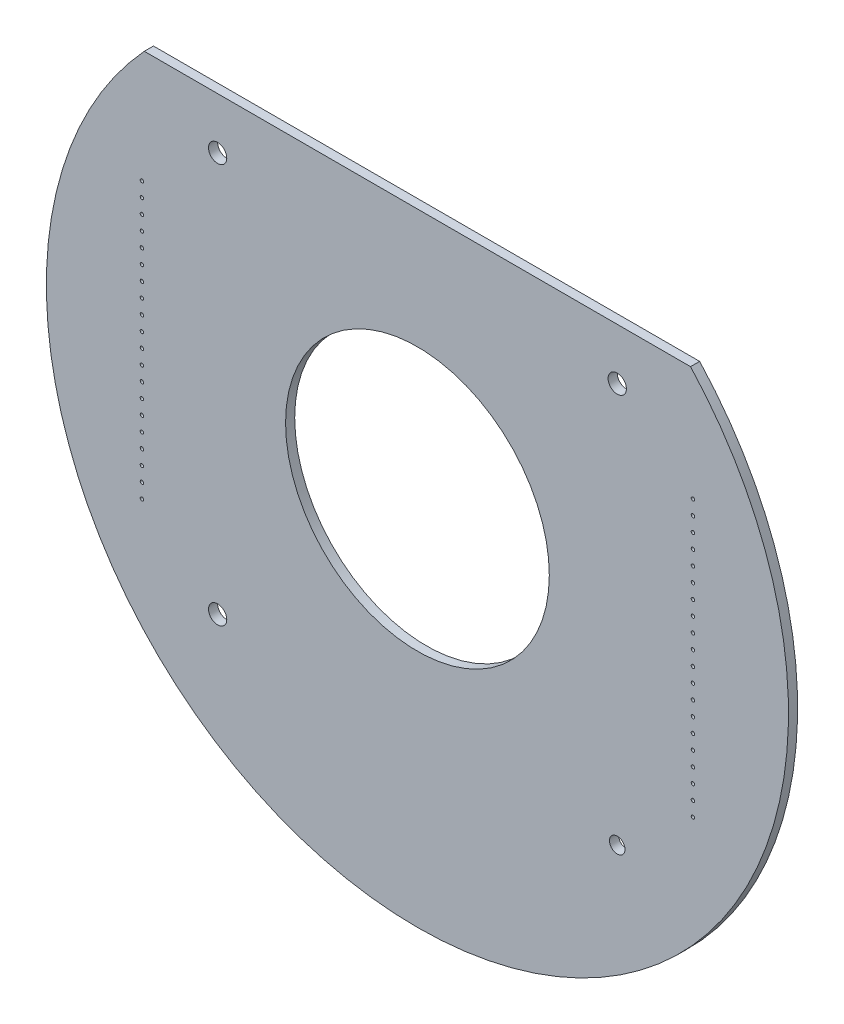
SolidWorks part; units mm, degrees
ref_plane "Front Plane" through (0, 0, 0) normal (0, 0, 1) x (1, 0, 0)
ref_plane "Top Plane" through (0, 0, 0) normal (0, 1, 0) x (1, 0, 0)
ref_plane "Right Plane" through (0, 0, 0) normal (1, 0, 0) x (0, 0, -1)
sketch "Sketch1" plane through (0, 0, 0) normal (0, 0, 1) x (1, 0, 0)
  circle A25 centre (0, 0) radius 65
extrude "Boss-Extrude1" add sketch "Sketch1" along normal blind 1.6
sketch "Sketch3" plane through (0, 0, 1.6) normal (0, 0, 1) x (1, 0, 0)
  circle A0 centre (48.26, -24.13) radius 0.3
  circle A1 centre (-48.26, -24.13) radius 0.3
  circle A2 centre (-48.26, -21.59) radius 0.3
  circle A3 centre (48.26, -21.59) radius 0.3
  circle A4 centre (-48.26, -19.05) radius 0.3
  circle A5 centre (48.26, -19.05) radius 0.3
  circle A6 centre (-48.26, -16.51) radius 0.3
  circle A7 centre (48.26, -16.51) radius 0.3
  circle A8 centre (-48.26, -13.97) radius 0.3
  circle A9 centre (48.26, -13.97) radius 0.3
  circle A10 centre (-48.26, -11.43) radius 0.3
  circle A11 centre (48.26, -11.43) radius 0.3
  circle A12 centre (-48.26, -8.89) radius 0.3
  circle A13 centre (48.26, -8.89) radius 0.3
  circle A14 centre (-48.26, -6.35) radius 0.3
  circle A15 centre (48.26, -6.35) radius 0.3
  circle A16 centre (-48.26, -3.81) radius 0.3
  circle A17 centre (48.26, -3.81) radius 0.3
  circle A18 centre (-48.26, -1.27) radius 0.3
  circle A19 centre (48.26, -1.27) radius 0.3
  circle A20 centre (-48.26, 1.27) radius 0.3
  circle A21 centre (48.26, 1.27) radius 0.3
  circle A22 centre (-48.26, 3.81) radius 0.3
  circle A23 centre (48.26, 3.81) radius 0.3
  circle A24 centre (-48.26, 6.35) radius 0.3
  circle A25 centre (48.26, 6.35) radius 0.3
  circle A26 centre (-48.26, 8.89) radius 0.3
  circle A27 centre (48.26, 8.89) radius 0.3
  circle A28 centre (-48.26, 11.43) radius 0.3
  circle A29 centre (48.26, 11.43) radius 0.3
  circle A30 centre (-48.26, 13.97) radius 0.3
  circle A31 centre (48.26, 13.97) radius 0.3
  circle A32 centre (-48.26, 16.51) radius 0.3
  circle A33 centre (48.26, 16.51) radius 0.3
  circle A34 centre (-48.26, 19.05) radius 0.3
  circle A35 centre (48.26, 19.05) radius 0.3
  circle A36 centre (-48.26, 21.59) radius 0.3
  circle A37 centre (48.26, 21.59) radius 0.3
  circle A38 centre (-48.26, 24.13) radius 0.3
  circle A39 centre (48.26, 24.13) radius 0.3
  dimension "D1" = 20
extrude "Cut-Extrude1" cut sketch "Sketch3" against normal up to vertex (1.6 mm away)
sketch "Sketch4" plane through (0, 0, 1.6) normal (0, 0, 1) x (1, 0, 0)
  line L0 (0, 0) -> (0, 65) construction
  line L5 (0, 65) -> (0, 70) construction
  line L7 (-50, 44) -> (50, 44)
  line L8 (-50, 44) -> (-50, 70)
  line L9 (-50, 70) -> (50, 70)
  line L10 (50, 44) -> (50, 70)
  line L11 (-50, 44) -> (50, 70) construction
  line L12 (-50, 70) -> (50, 44) construction
  point P2 (0, 57)
  dimension "D1" = 26
  dimension "D2" = 100
extrude "Cut-Extrude2" cut sketch "Sketch4" against normal blind 10
sketch "Sketch5" plane through (0, 0, 1.6) normal (0, 0, 1) x (1, 0, 0)
  line L1 (-35, -35) -> (35, -35) construction
  line L2 (-35, -35) -> (-35, 35) construction
  line L3 (-35, 35) -> (35, 35) construction
  line L4 (35, -35) -> (35, 35) construction
  line L5 (-35, -35) -> (35, 35) construction
  line L6 (-35, 35) -> (35, -35) construction
  circle A0 centre (-35, 35) radius 1.6
  circle A1 centre (35, 35) radius 1.6
  circle A2 centre (-35, -35) radius 1.6
  circle A3 centre (35, -35) radius 1.36
  point P0 (0, 0)
extrude "Cut-Extrude3" cut sketch "Sketch5" against normal blind 10
sketch "Sketch6" plane through (0, 0, 1.6) normal (0, 0, 1) x (1, 0, 0)
  circle A0 centre (0, 0) radius 23.1
extrude "Cut-Extrude4" cut sketch "Sketch6" against normal up to vertex (1.6 mm away)
